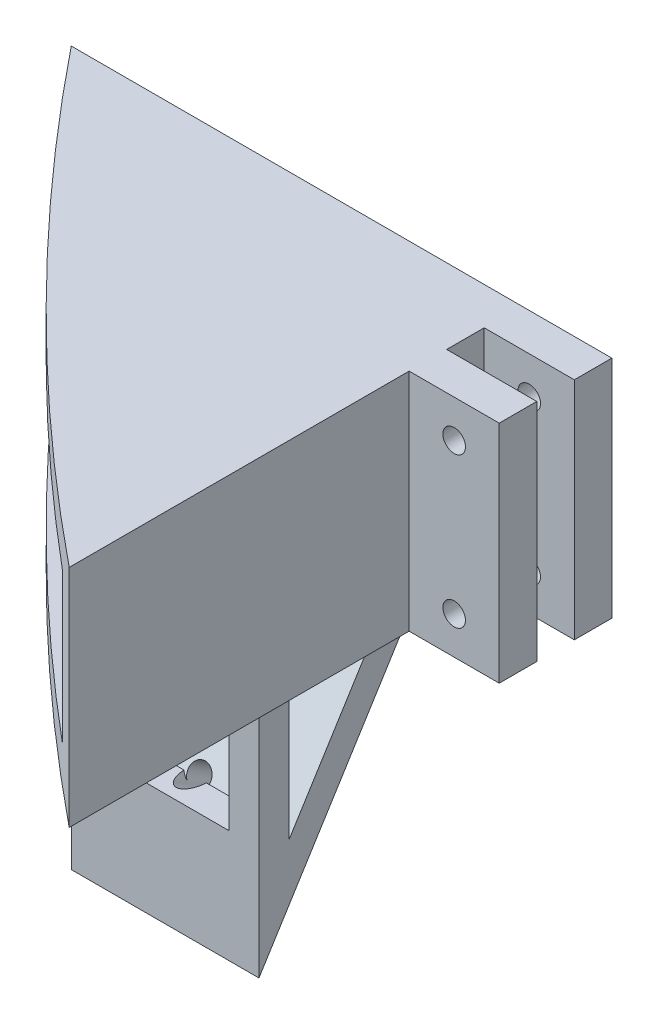
SolidWorks part; units mm, degrees
ref_plane "前视基准面" through (0, 0, 0) normal (0, 0, 1) x (1, 0, 0)
ref_plane "上视基准面" through (0, 0, 0) normal (0, 1, 0) x (1, 0, 0)
ref_plane "右视基准面" through (0, 0, 0) normal (1, 0, 0) x (0, 0, -1)
sketch "草图1" plane through (0, 0, 0) normal (0, 1, 0) x (1, 0, 0)
  line L0 (0, 0) -> (-70, 0)
  line L2 (0, 0) -> (0, -5)
  line L3 (0, -5) -> (-10, -5)
  line L4 (-10, -5) -> (-10, -10)
  line L5 (-10, -10) -> (0, -10)
  line L6 (0, -10) -> (0, -15)
  line L7 (0, -15) -> (-10, -15)
  line L8 (-10, -15) -> (-10, -60.2761)
  arc A0 (-70, 0) -> (-10, -60.2761) centre (241.8847, 250.4554) ccw
  dimension "D3" = 400
  dimension "D1" = 70
  dimension "D2" = 61.1
  dimension "D4" = 5
  dimension "D5" = 5
  dimension "D6" = 5
  dimension "D7" = 10
extrude "凸台-拉伸1" add sketch "草图1" along normal blind 30
sketch "草图2" plane through (0, 0, 0) normal (0, 0, -1) x (-1, 0, 0)
  line L0 (0, 15) -> (23.3117, 15) construction
  line L1 (0, 30) -> (0, 0) construction
  line L2 (0, 30) -> (70, 30) construction
  circle A0 centre (4, 25) radius 1.5
  circle A1 centre (4, 5) radius 1.5
  dimension "D1" = 3
  dimension "D2" = 4
  dimension "D3" = 5
extrude "切除-拉伸1" cut sketch "草图2" against normal through all both and the other way through all
ref_plane "基准面11" through (0, 30, 0) normal (0, 1, 0) x (1, 0, 0)
sketch "草图6" plane through (0, 30, 0) normal (0, 1, 0) x (1, 0, 0)
  line L4 (-15, -15) -> (-15, -5)
  line L5 (-59.3918, -5) -> (-65.918, -5)
  line L6 (-15, -49.6033) -> (-15, -15)
  line L7 (0, -5) -> (-59.3918, -5)
  line L8 (-15, -49.6033) -> (-15, -15)
  line L9 (-15, -5) -> (-59.3918, -5)
  line L10 (-15, -49.6033) -> (-15, -56.1555)
  arc A2 (-70, 0) -> (-10, -60.2761) centre (241.8847, 250.4554) ccw construction
  arc A3 (-59.3918, -5) -> (-15, -49.6033) centre (241.8847, 250.4554) ccw
  arc A7 (-70, 0) -> (-10, -60.2761) centre (241.8847, 250.4554) ccw
  arc A8 (-65.918, -5) -> (-15, -56.1555) centre (241.8847, 250.4554) ccw
  dimension "D2" = 0
  dimension "D1" = 5
ref_plane "基准面15" through (0, 15, 0) normal (0, 1, 0) x (1, 0, 0)
sketch "草图9" plane through (0, 15, 0) normal (0, 1, 0) x (1, 0, 0)
  line L10 (-65.918, -5) -> (-59.3918, -5)
  line L11 (-15, -49.6033) -> (-15, -56.1555)
  line L12 (-15, -49.6033) -> (-15, -15)
  line L13 (0, -5) -> (-59.3918, -5)
  line L14 (-15, -49.6033) -> (-15, -15)
  line L15 (-15, -5) -> (-59.3918, -5)
  line L16 (-15, -15) -> (-15, -5)
  arc A2 (-59.3918, -5) -> (-15, -49.6033) centre (241.8847, 250.4554) ccw
  arc A5 (-65.918, -5) -> (-15, -56.1555) centre (241.8847, 250.4554) ccw
  arc A6 (-65.918, -5) -> (-15, -56.1555) centre (241.8847, 250.4554) ccw
  dimension "D2" = 0
  dimension "D1" = 5
extrude "切除-拉伸6" cut sketch "草图9" against normal mid plane 20
sketch "草图11" plane through (0, 15, 0) normal (0, 1, 0) x (1, 0, 0)
  line L0 (-15, -5) -> (-23, -5)
  line L1 (-15, -5) -> (-59.3918, -5) construction
  line L2 (-15, -5) -> (-15, -10)
  line L3 (-15, -15) -> (-15, -5) construction
  line L4 (-15, -10) -> (-23, -5)
  dimension "D1" = 8
  dimension "D2" = 5
extrude "凸台-拉伸3" add sketch "草图11" along normal mid plane 25
ref_plane "基准面16" through (0, 0, 0) normal (0, 0, -1) x (-1, 0, 0)
sketch "草图12" plane through (0, 0, 0) normal (1, 0, 0) x (0, 0, -1)
  line L1 (-15, 30) -> (-10, 30)
  line L2 (-15, 30) -> (-15, 0)
  line L3 (-15, 0) -> (-10, 0)
  line L4 (-10, 30) -> (-10, 0)
  line L5 (-5, 0) -> (0, 0)
  line L6 (-5, 0) -> (-5, 30)
  line L7 (-5, 30) -> (0, 30)
  line L8 (0, 0) -> (0, 30)
extrude "凸台-拉伸4" add sketch "草图12" along normal blind 2
sketch "草图17" plane through (0, 0, 0) normal (0, -1, 0) x (1, 0, 0)
  line L0 (2, 0) -> (-70, 0) construction
  line L1 (-45, 0) -> (-20, 0)
  line L2 (-45, 0) -> (-45, 25)
  line L3 (-45, 25) -> (-20, 25)
  line L4 (-20, 0) -> (-20, 25)
  dimension "D1" = 25
extrude "凸台-拉伸7" add sketch "草图17" along normal blind 40
sketch "草图18" plane through (-45, 0, 0) normal (-1, 0, 0) x (0, 0, 1)
  line L10 (0, 0) -> (25, -40)
  line L11 (25, -40) -> (0, -40)
  line L12 (25, -40) -> (0, -40) construction
  line L13 (0, -40) -> (0, 0)
extrude "切除-拉伸9" cut sketch "草图18" against normal blind 50
sketch "草图21" plane through (0, 0, 0) normal (0, -0.53, -0.848) x (-1, 0, 0)
  line L0 (20, -47.1699) -> (20, 0) construction
  line L1 (20, -47.1699) -> (45, -47.1699) construction
  circle A0 centre (32.5, -22.1699) radius 1.5
  circle A1 centre (32.5, -12.1699) radius 1.5
  circle A2 centre (32.5, -32.1699) radius 1.5
  dimension "D1" = 12.5
  dimension "D3" = 10
  dimension "D2" = 25
  dimension "D4" = 10
extrude "切除-拉伸12" cut sketch "草图21" against normal blind 7
sketch "草图22" plane through (-45, 0, 0) normal (-1, 0, 0) x (0, 0, 1)
  line L0 (7.217, -4) -> (21, -4)
  line L1 (21, -4) -> (21, -26.0528)
  line L2 (21, -26.0528) -> (7.217, -4)
  line L4 (25, 0) -> (0, 0) construction
  line L5 (25, -40) -> (0, 0) construction
  line L6 (0, 0) -> (60.2761, 0) construction
  line L7 (25, -40) -> (25, 0) construction
  dimension "D1" = 4
  dimension "D2" = 4
  dimension "D3" = 4
extrude "切除-拉伸13" cut sketch "草图22" against normal blind 500
sketch "草图23" plane through (0, 0, 25) normal (0, 0, 1) x (1, 0, 0)
  line L0 (-20, 0) -> (-45, 0) construction
  line L1 (-41, -4) -> (-24, -4)
  line L2 (-41, -4) -> (-41, -25)
  line L3 (-41, -25) -> (-24, -25)
  line L4 (-24, -4) -> (-24, -25)
  line L5 (-45, -40) -> (-45, 0) construction
  line L6 (-20, -40) -> (-20, 0) construction
  line L7 (-20, -40) -> (-45, -40) construction
  dimension "D1" = 4
  dimension "D2" = 4
  dimension "D3" = 4
  dimension "D4" = 15
extrude "切除-拉伸14" cut sketch "草图23" against normal blind 4
